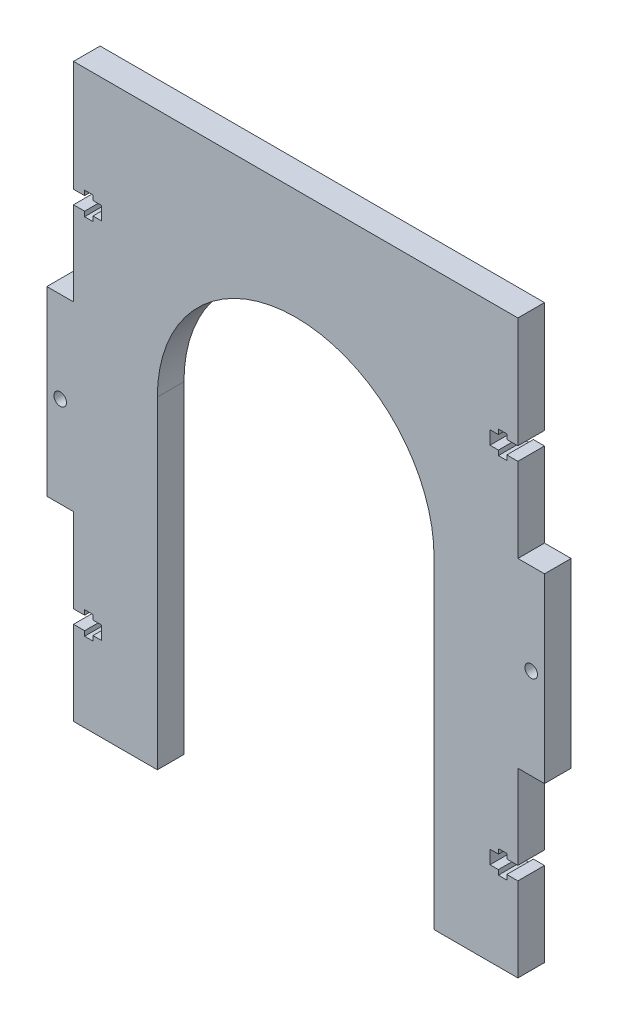
SolidWorks part; units mm, degrees
ref_plane "Front Plane" through (0, 0, 0) normal (0, 0, 1) x (1, 0, 0)
ref_plane "Top Plane" through (0, 0, 0) normal (0, 1, 0) x (1, 0, 0)
ref_plane "Right Plane" through (0, 0, 0) normal (1, 0, 0) x (0, 0, -1)
sketch "Sketch1" plane through (0, 0, 0) normal (0, 0, 1) x (1, 0, 0)
  line L0 (59.35, 0) -> (59.35, 50000) construction
  line L1 (0, 0) -> (118.7, 0)
  line L2 (0, 0) -> (0, 6.35)
  line L3 (0, 6.35) -> (118.7, 6.35)
  line L4 (118.7, 0) -> (118.7, 6.35)
  line L5 (0, 0) -> (6.35, 0)
  line L6 (0, 0) -> (0, -43.3333)
  line L7 (0, -43.3333) -> (6.35, -43.3333)
  line L8 (6.35, 0) -> (6.35, -43.3333)
  line L9 (0, -43.3333) -> (6.35, -43.3333)
  line L10 (0, -43.3333) -> (0, -86.6667)
  line L11 (0, -86.6667) -> (6.35, -86.6667)
  line L12 (6.35, -43.3333) -> (6.35, -86.6667)
  line L13 (0, -86.6667) -> (6.35, -86.6667)
  line L14 (0, -86.6667) -> (0, -130)
  line L15 (0, -130) -> (6.35, -130)
  line L16 (6.35, -86.6667) -> (6.35, -130)
  line L17 (6.35, -130) -> (26.35, -130)
  line L18 (26.35, -130) -> (26.35, -53)
  line L19 (112.35, -20) -> (6.35, -20) construction
  line L20 (0, -43.3333) -> (6.35, -86.6667) construction
  line L21 (0, -21.6667) -> (13, -21.6667) construction
  line L22 (13, -20.0667) -> (13, -23.2667)
  line L23 (9, -18.9167) -> (11, -18.9167)
  line L24 (9, -18.9167) -> (9, -24.4167)
  line L25 (9, -24.4167) -> (11, -24.4167)
  line L26 (11, -18.9167) -> (11, -24.4167)
  line L27 (9, -18.9167) -> (11, -24.4167) construction
  line L28 (9, -24.4167) -> (11, -18.9167) construction
  line L29 (13, -20.0667) -> (0, -20.0667)
  line L30 (13, -23.2667) -> (0, -23.2667)
  line L31 (3.175, -65) -> (115.525, -65) construction
  line L32 (9, -105.5833) -> (11, -111.0833) construction
  line L33 (9, -111.0833) -> (11, -105.5833) construction
  line L34 (0, -108.3333) -> (13, -108.3333) construction
  line L35 (13, -106.7333) -> (0, -106.7333)
  line L36 (13, -109.9333) -> (0, -109.9333)
  line L37 (11, -111.0833) -> (11, -105.5833)
  line L38 (9, -105.5833) -> (11, -105.5833)
  line L39 (9, -111.0833) -> (9, -105.5833)
  line L40 (9, -111.0833) -> (11, -111.0833)
  line L41 (13, -109.9333) -> (13, -106.7333)
  line L42 (6.35, 0) -> (6.35, 6.35)
  line L43 (118.7, -108.3333) -> (105.7, -108.3333) construction
  line L44 (109.7, -111.0833) -> (107.7, -105.5833) construction
  line L45 (109.7, -105.5833) -> (107.7, -111.0833) construction
  line L46 (109.7, -24.4167) -> (107.7, -18.9167) construction
  line L47 (109.7, -18.9167) -> (107.7, -24.4167) construction
  line L48 (118.7, -21.6667) -> (105.7, -21.6667) construction
  line L49 (118.7, -43.3333) -> (112.35, -86.6667) construction
  line L50 (112.35, 0) -> (112.35, 6.35)
  line L51 (105.7, -109.9333) -> (105.7, -106.7333)
  line L52 (109.7, -111.0833) -> (107.7, -111.0833)
  line L53 (109.7, -111.0833) -> (109.7, -105.5833)
  line L54 (109.7, -105.5833) -> (107.7, -105.5833)
  line L55 (107.7, -111.0833) -> (107.7, -105.5833)
  line L56 (105.7, -109.9333) -> (118.7, -109.9333)
  line L57 (105.7, -106.7333) -> (118.7, -106.7333)
  line L58 (105.7, -23.2667) -> (118.7, -23.2667)
  line L59 (105.7, -20.0667) -> (118.7, -20.0667)
  line L60 (107.7, -18.9167) -> (107.7, -24.4167)
  line L61 (109.7, -24.4167) -> (107.7, -24.4167)
  line L62 (109.7, -18.9167) -> (109.7, -24.4167)
  line L63 (109.7, -18.9167) -> (107.7, -18.9167)
  line L64 (105.7, -20.0667) -> (105.7, -23.2667)
  line L65 (92.35, -130) -> (92.35, -53)
  line L66 (112.35, -130) -> (92.35, -130)
  line L67 (112.35, -86.6667) -> (112.35, -130)
  line L68 (118.7, -130) -> (112.35, -130)
  line L69 (118.7, -86.6667) -> (118.7, -130)
  line L70 (118.7, -86.6667) -> (112.35, -86.6667)
  line L71 (112.35, -43.3333) -> (112.35, -86.6667)
  line L72 (118.7, -86.6667) -> (112.35, -86.6667)
  line L73 (118.7, -43.3333) -> (118.7, -86.6667)
  line L74 (118.7, -43.3333) -> (112.35, -43.3333)
  line L75 (112.35, 0) -> (112.35, -43.3333)
  line L76 (118.7, -43.3333) -> (112.35, -43.3333)
  line L77 (118.7, 0) -> (118.7, -43.3333)
  line L78 (118.7, 0) -> (112.35, 0)
  line L79 (118.7, 0) -> (118.7, 6.35)
  arc A0 (26.35, -53) -> (92.35, -53) centre (59.35, -53) cw
  circle A1 centre (3.175, -65) radius 1.5
  circle A2 centre (115.525, -65) radius 1.5
  point P14 (59.35, 0)
  point P24 (10, -21.6667)
  point P44 (10, -108.3333)
  point P53 (59.35, -65)
  point P78 (108.7, -108.3333)
  point P79 (108.7, -21.6667)
  dimension "D5" = 20
  dimension "D6" = 3
  dimension "D1" = 43.3333
  dimension "D2" = 6.35
  dimension "D3" = 53
  dimension "D4" = 20
  dimension "D7" = 13
  dimension "D8" = 2
  dimension "D9" = 2
  dimension "D10" = 5.5
  dimension "D11" = 3.2
extrude "Boss-Extrude1" add sketch "Sketch1" along normal blind 6.35 contours L1 L50 L3 L42 | L18 A0 L65 L66 L67 L56 L53 L52 L55 L51 L57 L54 L71 L75 L58 L62 L61 L60 L64 L59 L63 L1 L8 L29 L24 L23 L26 L22 L30 L25 L12 L16 L35 L39 L38 L37 | L12 L7 L10 L11 A1 | L73 L74 L71 L70 A2
